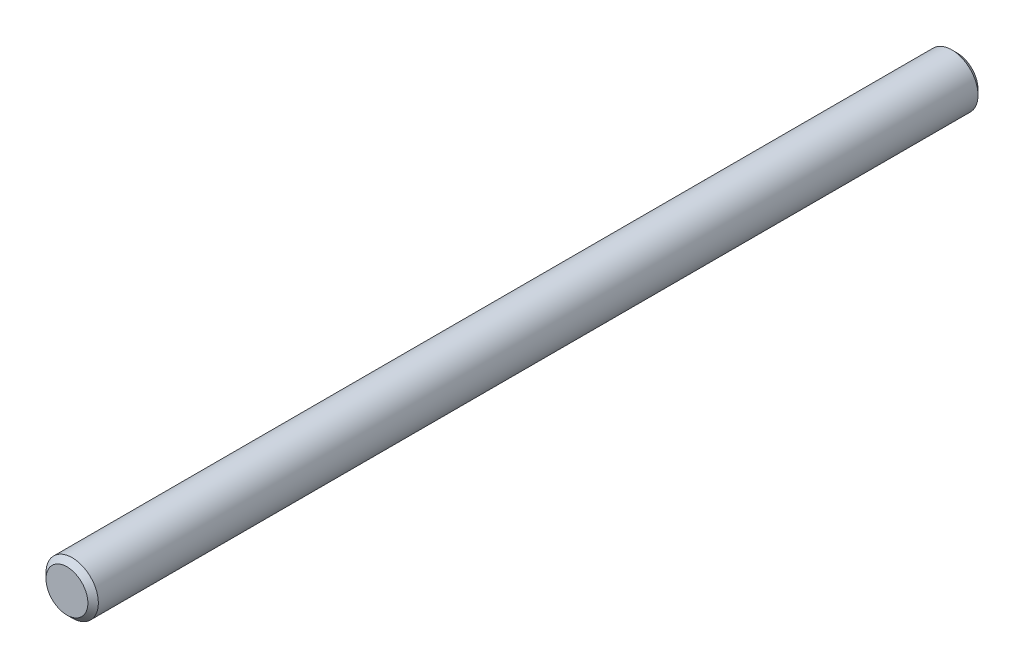
SolidWorks part; units mm, degrees
ref_plane "Front Plane" through (0, 0, 0) normal (0, 0, 1) x (1, 0, 0)
ref_plane "Top Plane" through (0, 0, 0) normal (0, 1, 0) x (1, 0, 0)
ref_plane "Right Plane" through (0, 0, 0) normal (1, 0, 0) x (0, 0, -1)
sketch "Sketch1" plane through (0, 0, 0) normal (1, 0, 0) x (0, 0, -1)
  line L0 (-5.6542, 0) -> (6.1308, 0) construction
  line L2 (0, 0) -> (17, 0)
  line L3 (0, 0) -> (0, 0.5)
  line L4 (0, 0.5) -> (17, 0.5)
  line L5 (17, 0) -> (17, 0.5)
  dimension "D1" = 1
  dimension "D2" = 17
revolve "Revolve1" add sketch "Sketch1" angle 360 about L0
chamfer "Chamfer1" distance 0.1 angle 45 2 edges at (0.5, 0, -17) (0.5, 0, 0)
